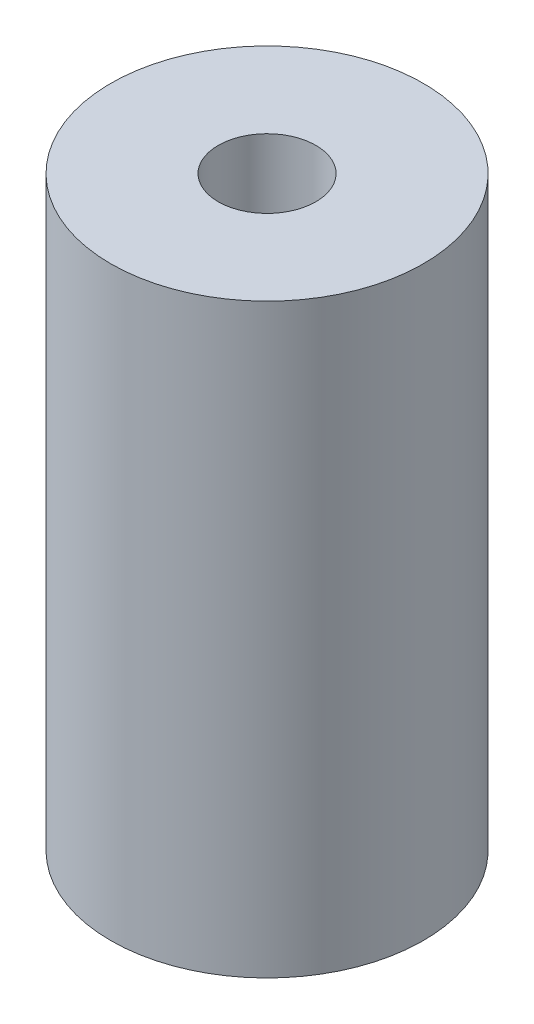
SolidWorks part; units mm, degrees
ref_plane "Front Plane" through (0, 0, 0) normal (0, 0, 1) x (1, 0, 0)
ref_plane "Top Plane" through (0, 0, 0) normal (0, 1, 0) x (1, 0, 0)
ref_plane "Right Plane" through (0, 0, 0) normal (1, 0, 0) x (0, 0, -1)
sketch "SketchCylinder" plane through (0, 0, 0) normal (0, 1, 0) x (1, 0, 0)
  circle A0 centre (0, 0) radius 1.6
  circle A1 centre (0, 0) radius 0.5
extrude "BossExtrudeCylinder" add sketch "SketchCylinder" along normal blind 6
